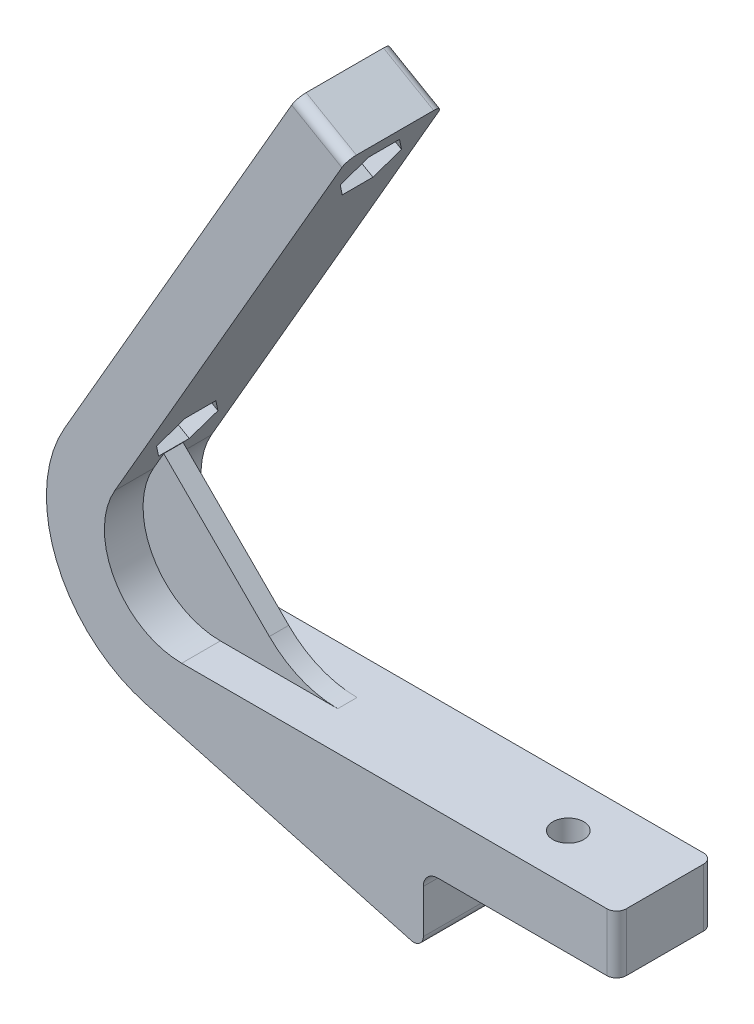
SolidWorks part; units mm, degrees
ref_plane "前视基准面" through (0, 0, 0) normal (0, 0, 1) x (1, 0, 0)
ref_plane "上视基准面" through (0, 0, 0) normal (0, 1, 0) x (1, 0, 0)
ref_plane "右视基准面" through (0, 0, 0) normal (1, 0, 0) x (0, 0, -1)
sketch "草图1" plane through (0, 0, 0) normal (0, 0, 1) x (1, 0, 0)
  line L1 (-41.9282, 12) -> (-17.9282, 53.5692)
  line L2 (-17.9282, 53.5692) -> (-23.1244, 56.5692)
  line L3 (-23.1244, 56.5692) -> (-47.1244, 15)
  line L5 (10, -6) -> (10, 0)
  line L6 (10, 0) -> (-35, 0)
  line L9 (-10, -12) -> (-10, -6)
  line L10 (-10, -6) -> (10, -6)
  line L11 (-11.2625, -12.9649) -> (-38.6744, -5.5092)
  arc A0 (-35, 0) -> (-41.9282, 12) centre (-35, 8) cw
  arc A1 (-38.6744, -5.5092) -> (-47.1244, 15) centre (-35, 8) cw
  arc A2 (-10, -12) -> (-11.2625, -12.9649) centre (-11, -12) cw
  point P14 (-9.9233, -16.9042)
  dimension "D5" = 8
  dimension "D9" = 1
  dimension "D1" = 10
  dimension "D2" = 35
  dimension "D3" = 6
  dimension "D4" = 60
  dimension "D6" = 48
  dimension "D7" = 20
  dimension "D8" = 6
  dimension "D10" = 6
extrude "凸台-拉伸1" add sketch "草图1" along normal mid plane 10
sketch "草图2" plane through (0, 0, 0) normal (0, 1, 0) x (1, 0, 0)
  circle A0 centre (0, 0) radius 1.6
  dimension "D1" = 3.2
extrude "切除-拉伸1" cut sketch "草图2" against normal through all
sketch "草图3" plane through (-41.8385, 24.1554, 0) normal (-0.866, 0.5, 0) x (0, 0, 1)
  line L0 (5, -10.5718) -> (-5, -10.5718) construction
  circle A0 centre (0, 32.4282) radius 1.6
  circle A1 centre (0, -5.5718) radius 1.6
  point P4 (0, 30.7365)
  point P7 (1.9594, -7.5718)
  dimension "D1" = 3.2
  dimension "D2" = 38
  dimension "D3" = 5
extrude "切除-拉伸2" cut sketch "草图3" against normal blind 6
sketch "草图4" plane through (-36.6423, 21.1554, 0) normal (0.866, -0.5, 0) x (0, 0, -1)
  line L1 (1.5877, 35.1782) -> (-1.5877, 35.1782)
  line L2 (-1.5877, 35.1782) -> (-3.1754, 32.4282)
  line L3 (-3.1754, 32.4282) -> (-1.5877, 29.6782)
  line L4 (-1.5877, 29.6782) -> (1.5877, 29.6782)
  line L5 (1.5877, 29.6782) -> (3.1754, 32.4282)
  line L6 (3.1754, 32.4282) -> (1.5877, 35.1782)
  line L7 (1.5877, -2.8218) -> (-1.5877, -2.8218)
  line L8 (-1.5877, -2.8218) -> (-3.1754, -5.5718)
  line L9 (-3.1754, -5.5718) -> (-1.5877, -8.3218)
  line L10 (-1.5877, -8.3218) -> (1.5877, -8.3218)
  line L11 (1.5877, -8.3218) -> (3.1754, -5.5718)
  line L12 (3.1754, -5.5718) -> (1.5877, -2.8218)
  circle A0 centre (0, 32.4282) radius 2.75 construction
  circle A1 centre (0, -5.5718) radius 2.75 construction
  dimension "D1" = 5.5
  dimension "D2" = 5.5
extrude "切除-拉伸3" cut sketch "草图4" against normal blind 2
fillet "圆角1" radius 1 4 edges at (-20.5263, 55.0692, -5) (-20.5263, 55.0692, 5) (10, -3, -5) (10, -3, 5)
sketch "草图6" plane through (0, 0, 0) normal (0, 0, 1) x (1, 0, 0)
  line L0 (-41.9282, 12) -> (-40.8564, 13.8564)
  line L1 (-41.9282, 12) -> (-18.4282, 52.7032) construction
  line L3 (-35, 0) -> (-27, 0)
  line L4 (9, 0) -> (-35, 0) construction
  line L5 (-40.8564, 13.8564) -> (-27, 0)
  arc A0 (-35, 0) -> (-41.9282, 12) centre (-35, 8) cw
  arc A1 (-41.9282, 12) -> (-35, 0) centre (-35, 8) ccw construction
  point P7 (-27.4315, 0)
  dimension "D1" = 45
extrude "凸台-拉伸2" add sketch "草图6" along normal mid plane 2
fillet "圆角2" radius 1.5 1 edges at (-10, -6, 0)
fillet "圆角3" radius 10 1 edges at (-27, 0, 0)
